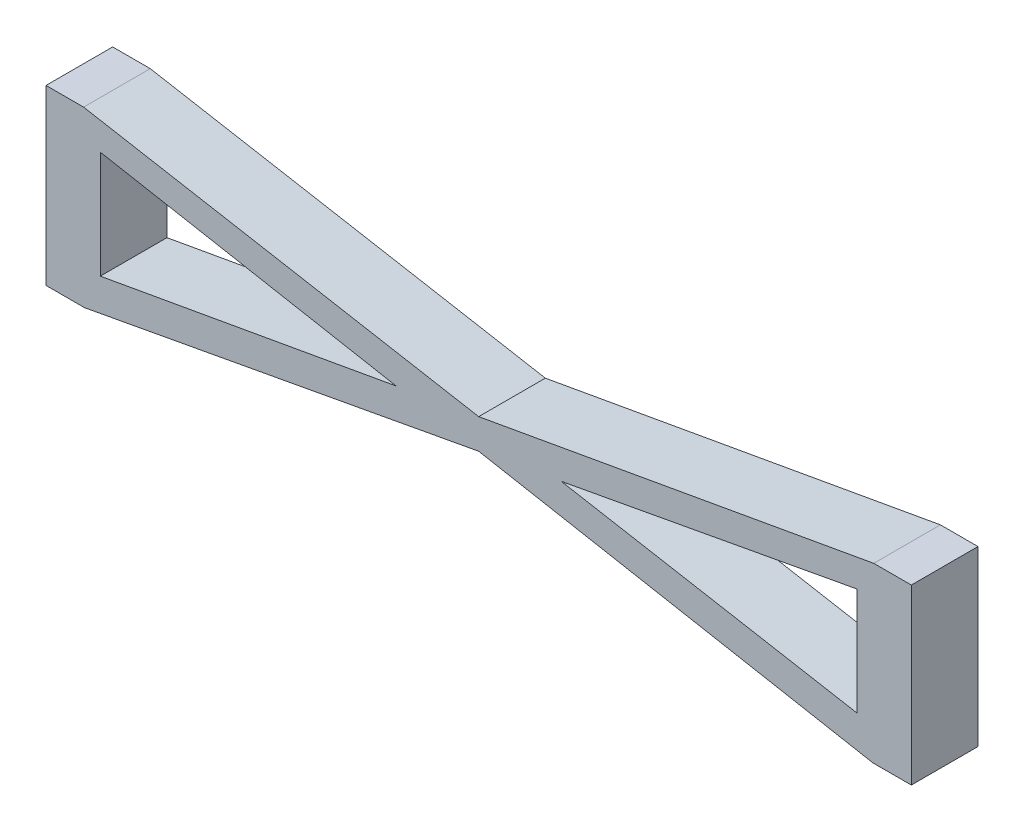
SolidWorks part; units mm, degrees
ref_plane "Front Plane" through (0, 0, 0) normal (0, 0, 1) x (1, 0, 0)
ref_plane "Top Plane" through (0, 0, 0) normal (0, 1, 0) x (1, 0, 0)
ref_plane "Right Plane" through (0, 0, 0) normal (1, 0, 0) x (0, 0, -1)
sketch "Sketch1" plane through (0, 0, 0) normal (0, 0, 1) x (1, 0, 0)
  line L0 (0, 0) -> (246.998, 49.45) construction
  line L1 (0, 0) -> (10.9854, 0)
  line L2 (0, 0) -> (0, 49.45)
  line L3 (0, 49.45) -> (10.7305, 49.45)
  line L4 (246.998, 0) -> (246.998, 49.45)
  line L5 (246.998, 0) -> (0, 49.45) construction
  line L6 (15.5, 40.7057) -> (99.9299, 25.1203)
  line L7 (10.7305, 49.45) -> (123.499, 29.3262)
  line L8 (236.2675, 49.45) -> (123.499, 29.3262)
  line L9 (231.498, 40.7057) -> (147.0681, 25.1203)
  line L10 (236.2675, 49.45) -> (246.998, 49.45)
  line L12 (15.5, 10.0536) -> (15.5, 40.7057)
  line L14 (231.498, 10.0536) -> (231.498, 40.7057)
  line L16 (236.0126, 0) -> (246.998, 0)
  line L17 (123.499, 20.7695) -> (236.0126, 0)
  line L18 (99.9299, 25.1203) -> (15.5, 10.0536)
  line L19 (147.0681, 25.1203) -> (231.498, 10.0536)
  line L20 (123.499, 20.7695) -> (10.9854, 0)
  point P17 (0, 0)
  dimension "D1" = 246.998
  dimension "D2" = 49.45
  dimension "D3" = 15.5
extrude "Boss-Extrude1" add sketch "Sketch1" along normal blind 19.0273
